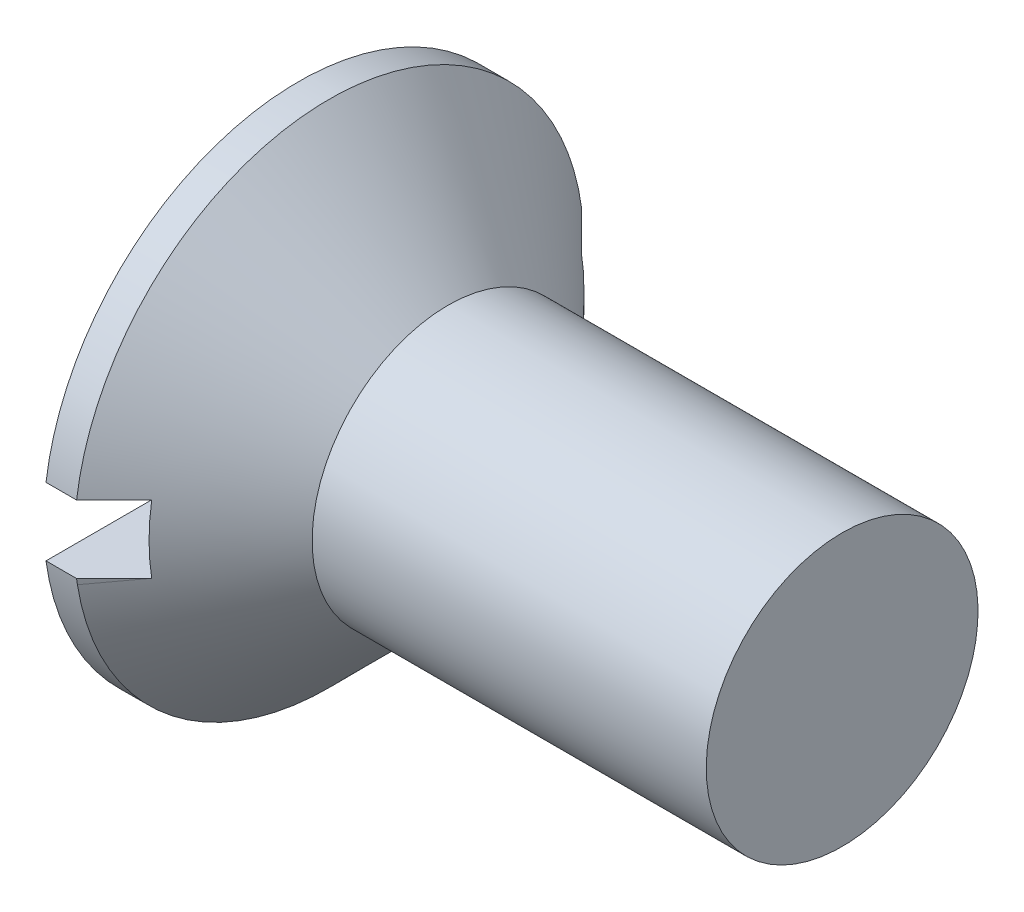
SolidWorks part; units mm, degrees
material "Plain Carbon Steel"
ref_plane "Front Plane" through (0, 0, 0) normal (0, 0, 1) x (1, 0, 0)
ref_plane "Top Plane" through (0, 0, 0) normal (0, 1, 0) x (1, 0, 0)
ref_plane "Right Plane" through (0, 0, 0) normal (1, 0, 0) x (0, 0, -1)
sketch "Sketch1" plane through (0, 0, 0) normal (0, 0, 1) x (1, 0, 0)
  line L0 (0, 0) -> (0, 3.75)
  line L1 (0, 3.75) -> (0.45, 3.75)
  line L2 (0.45, 3.75) -> (2.2, 2)
  line L3 (2.2, 2) -> (8, 2)
  line L4 (8, 2) -> (8, 0)
  line L5 (8, 0) -> (0, 0) construction
  line L6 (0, 0) -> (8, 0)
  dimension "D1" = 45
  dimension "D2" = 4
  dimension "D3" = 7.5
  dimension "D4" = 2.2
  dimension "D5" = 8
revolve "Revolve1" add sketch "Sketch1" angle 360 about L5
sketch "Sketch2" plane through (0, 0, 0) normal (-1, 0, 0) x (0, 0, 1)
  line L0 (3.75, 0) -> (-3.75, 0) construction
  line L1 (-3.75, 0.5) -> (3.75, 0.5)
  line L2 (-3.75, 0.5) -> (-3.75, -0.5)
  line L3 (-3.75, -0.5) -> (3.75, -0.5)
  line L4 (3.75, 0.5) -> (3.75, -0.5)
  circle A0 centre (0, 0) radius 3.75 construction
  dimension "D1" = 1
extrude "Cut-Extrude1" cut sketch "Sketch2" against normal blind 1
